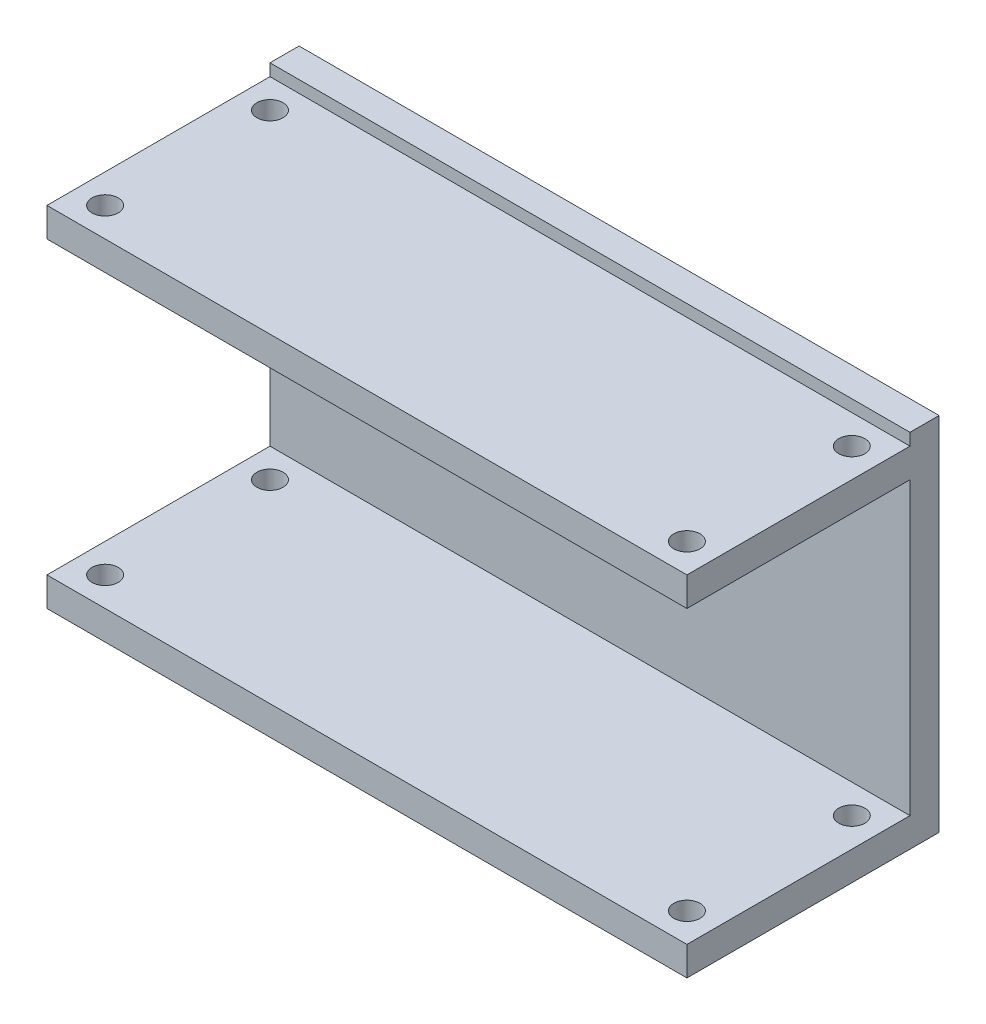
SolidWorks part; units mm, degrees
ref_plane "Front Plane" through (0, 0, 0) normal (0, 0, 1) x (1, 0, 0)
ref_plane "Top Plane" through (0, 0, 0) normal (0, 1, 0) x (1, 0, 0)
ref_plane "Right Plane" through (0, 0, 0) normal (1, 0, 0) x (0, 0, -1)
sketch "Sketch1" plane through (0, 0, 0) normal (0, 1, 0) x (1, 0, 0)
  line L0 (0, 0) -> (0, 18.1718) construction
  line L1 (-33, 11.5) -> (33, 11.5)
  line L2 (-33, 11.5) -> (-33, -11.5)
  line L3 (-33, -11.5) -> (33, -11.5)
  line L4 (33, 11.5) -> (33, -11.5)
  line L5 (-33, 11.5) -> (33, -11.5) construction
  line L6 (-33, -11.5) -> (33, 11.5) construction
  circle A2 centre (-30, -8.5) radius 1.35
  circle A3 centre (-30, 8.5) radius 1.35
  circle A4 centre (30, -8.5) radius 1.35
  circle A5 centre (30, 8.5) radius 1.35
  point P0 (0, 0)
  point P16 (0, 0)
  point P17 (0, 0)
  dimension "D1" = 2.7
  dimension "D2" = 3
  dimension "D4" = 3
  dimension "D5" = 3
  dimension "D6" = 60
  dimension "D3" = 17
extrude "Boss-Extrude1" add sketch "Sketch1" along normal blind 3
ref_plane "Plane1" through (0, 18, 0) normal (0, 1, 0) x (1, 0, 0)
sketch "Sketch2" plane through (0, 0, -11.5) normal (0, 0, -1) x (-1, 0, 0)
  line L1 (-33, 0) -> (33, 0)
  line L2 (-33, 0) -> (-33, 37.2364)
  line L3 (-33, 37.2364) -> (33, 37.2364)
  line L4 (33, 0) -> (33, 37.2364)
  point P5 (33, 0)
extrude "Boss-Extrude2" add sketch "Sketch2" along normal blind 3
mirror "Mirror2" about plane through (0, 18, 0) normal (0, 1, 0) of "Boss-Extrude1"
